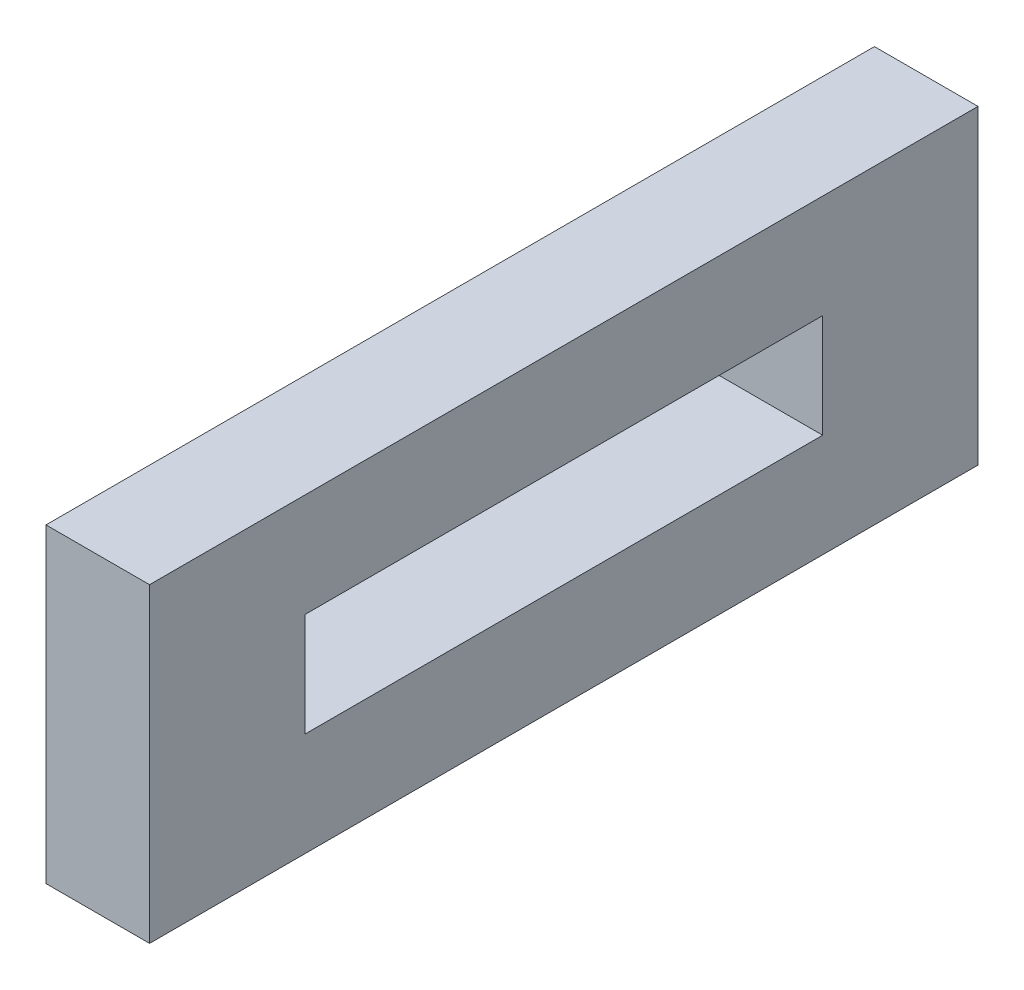
SolidWorks part; units mm, degrees
ref_plane "Front Plane" through (0, 0, 0) normal (0, 0, 1) x (1, 0, 0)
ref_plane "Top Plane" through (0, 0, 0) normal (0, 1, 0) x (1, 0, 0)
ref_plane "Right Plane" through (0, 0, 0) normal (1, 0, 0) x (0, 0, -1)
sketch "Sketch2" plane through (0, 0, 0) normal (1, 0, 0) x (0, 0, -1)
  line L1 (-40, 15) -> (40, 15)
  line L2 (-40, 15) -> (-40, -15)
  line L3 (-40, -15) -> (40, -15)
  line L4 (40, 15) -> (40, -15)
  line L5 (-40, 15) -> (40, -15) construction
  line L6 (-40, -15) -> (40, 15) construction
  line L7 (-25, 5) -> (25, 5)
  line L8 (-25, 5) -> (-25, -5)
  line L9 (-25, -5) -> (25, -5)
  line L10 (25, 5) -> (25, -5)
  line L11 (-25, 5) -> (25, -5) construction
  line L12 (-25, -5) -> (25, 5) construction
  point P0 (0, 0)
  point P6 (0, 0)
  dimension "D1" = 80
  dimension "D2" = 30
  dimension "D3" = 50
  dimension "D4" = 10
extrude "Boss-Extrude1" add sketch "Sketch2" along normal blind 10
